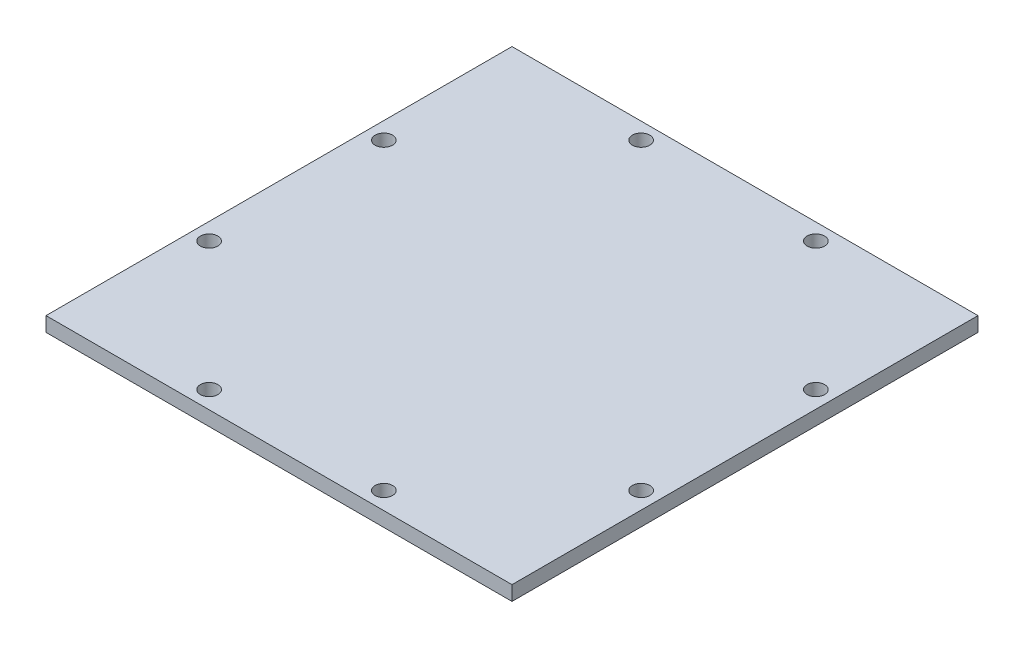
SolidWorks part; units mm, degrees
ref_plane "Front Plane" through (0, 0, 0) normal (0, 0, 1) x (1, 0, 0)
ref_plane "Top Plane" through (0, 0, 0) normal (0, 1, 0) x (1, 0, 0)
ref_plane "Right Plane" through (0, 0, 0) normal (1, 0, 0) x (0, 0, -1)
sketch "Эскиз1" plane through (0, 0, 0) normal (0, 1, 0) x (1, 0, 0)
  line L1 (-40, -40) -> (40, -40)
  line L2 (-40, -40) -> (-40, 40)
  line L3 (-40, 40) -> (40, 40)
  line L4 (40, -40) -> (40, 40)
  line L5 (-40, -40) -> (40, 40) construction
  line L6 (-40, 40) -> (40, -40) construction
  point P0 (0, 0)
  dimension "D1" = 80
extrude "Бобышка-Вытянуть1" add sketch "Эскиз1" along normal blind 2.5
sketch "Эскиз2" plane through (0, 2.5, 0) normal (0, 1, 0) x (1, 0, 0)
  line L0 (-40, -40) -> (40, -40) construction
  line L1 (-40, 40) -> (-40, -40) construction
  circle A0 centre (-15, -37) radius 1.5
  circle A1 centre (15, -37) radius 1.5
  dimension "D4" = 3
  dimension "D5" = 3
  dimension "D1" = 3
  dimension "D2" = 30
  dimension "D3" = 25
  dimension "D6" = 3
extrude "Вырез-Вытянуть1" cut sketch "Эскиз2" against normal blind 10
pattern_circular "Круговой массив1" count 4 over 360 about axis through (0, 0, -0.0819) along (0, 1, 0) of "Вырез-Вытянуть1"
sketch "Эскиз3" plane through (0, 2.5, 0) normal (0, 1, 0) x (1, 0, 0)
  circle A0 centre (-15, -37) radius 1.5 construction
  point P0 (0, 0)
  dimension "D1" = 37
